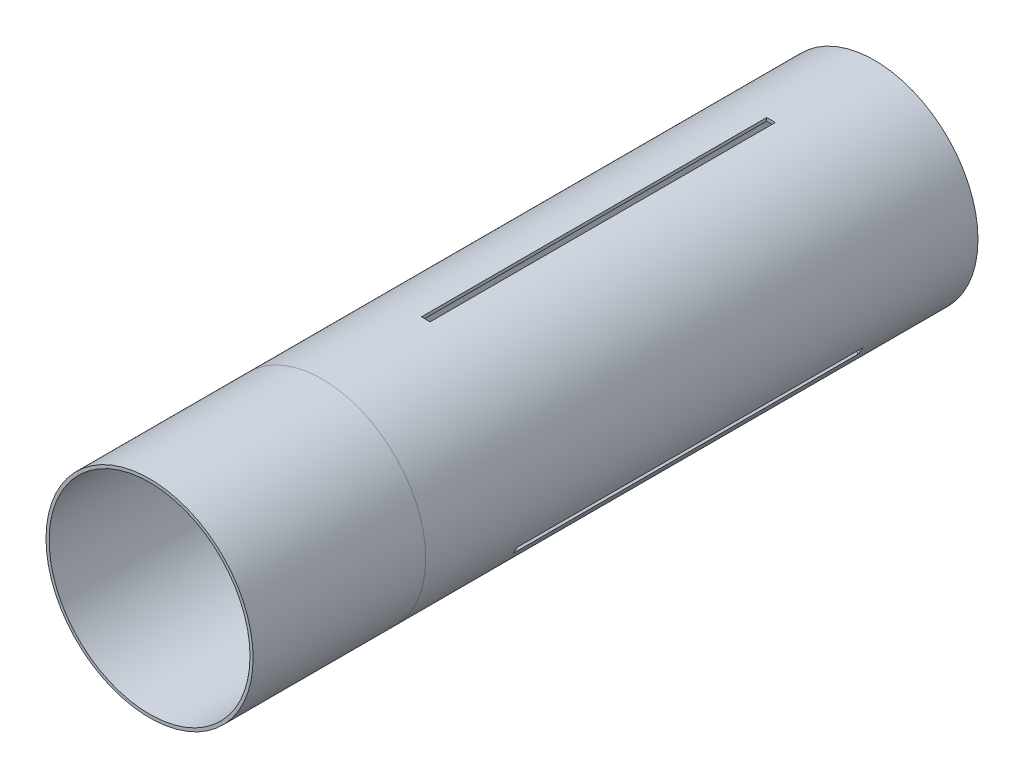
SolidWorks part; units mm, degrees
ref_plane "Plan de face" through (0, 0, 0) normal (0, 0, 1) x (1, 0, 0)
ref_plane "Plan de dessus" through (0, 0, 0) normal (0, 1, 0) x (1, 0, 0)
ref_plane "Plan de droite" through (0, 0, 0) normal (1, 0, 0) x (0, 0, -1)
sketch "Esquisse2" plane through (0, 0, 0) normal (0, 0, 1) x (1, 0, 0)
  circle A0 centre (0, 0) radius 76.1746
  circle A1 centre (0, 0) radius 73.914
  dimension "D1" = 152.3492
  dimension "D2" = 147.828
extrude "Boss.-Extru.1" add sketch "Esquisse2" along normal blind 406.4
sketch "Esquisse3" plane through (0, 0, 406.4) normal (0, 0, 1) x (1, 0, 0)
  circle A0 centre (0, 0) radius 76.2
  circle A1 centre (0, 0) radius 73.914
  dimension "D1" = 147.828
extrude "Boss.-Extru.2" add sketch "Esquisse3" along normal blind 127
sketch "Esquisse4" plane through (0, 0, 0) normal (0, 1, 0) x (1, 0, 0)
  line L0 (0, 0) -> (0, -76.2)
  line L1 (0, -76.2) -> (0, -203.2)
  line L2 (0, -76.2) -> (-3.175, -76.2)
  line L4 (3.175, -330.2) -> (-3.175, -330.2)
  line L5 (3.175, -330.2) -> (3.175, -76.2)
  line L6 (3.175, -76.2) -> (-3.175, -76.2)
  line L7 (-3.175, -330.2) -> (-3.175, -76.2)
  line L8 (3.175, -330.2) -> (-3.175, -76.2) construction
  line L9 (3.175, -76.2) -> (-3.175, -330.2) construction
  dimension "D1" = 76.2
  dimension "D2" = 127
  dimension "D3" = 3.175
extrude "Enlèv. mat.-Extru.1" cut sketch "Esquisse4" along normal blind 96.774
pattern_circular "Répétition circulaire1" count 3 every 120 about axis through (0, 0, 0) along (0, 0, 1) of "Enlèv. mat.-Extru.1"
